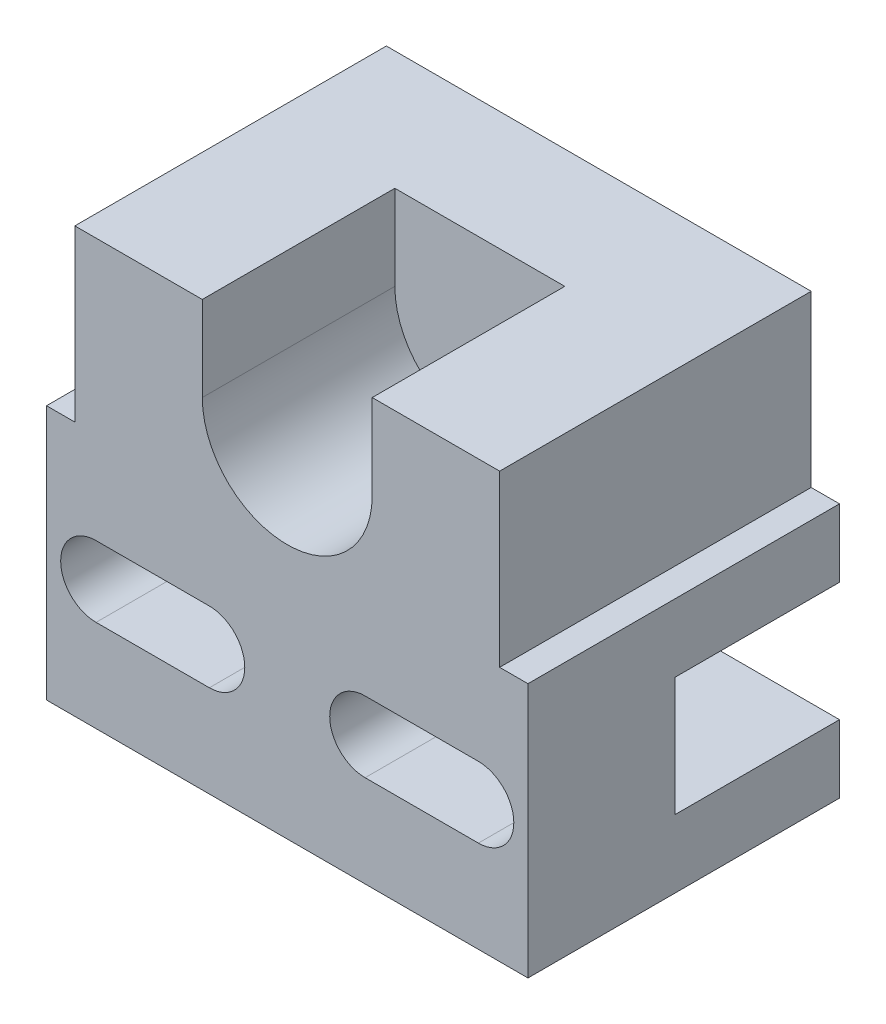
SolidWorks part; units mm, degrees
ref_plane "Front Plane" through (0, 0, 0) normal (0, 0, 1) x (1, 0, 0)
ref_plane "Top Plane" through (0, 0, 0) normal (0, 1, 0) x (1, 0, 0)
ref_plane "Right Plane" through (0, 0, 0) normal (1, 0, 0) x (0, 0, -1)
sketch "Sketch1" plane through (0, 0, 0) normal (0, 0, 1) x (1, 0, 0)
  line L0 (55, 0) -> (-55, 0) construction
  line L1 (-8.5, 0) -> (8.5, 0)
  line L2 (-8.5, 0) -> (-8.5, 9)
  line L3 (-7.5, 15) -> (7.5, 15)
  line L4 (8.5, 0) -> (8.5, 9)
  line L5 (-7.5, 15) -> (-7.5, 9)
  line L6 (-7.5, 9) -> (-8.5, 9)
  line L7 (8.5, 9) -> (7.5, 9)
  line L8 (7.5, 9) -> (7.5, 15)
  dimension "D1" = 17
  dimension "D2" = 15
  dimension "D3" = 15
  dimension "D4" = 9
extrude "Boss-Extrude1" add sketch "Sketch1" along normal blind 11
sketch "Sketch2" plane through (0, 0, 11) normal (0, 0, 1) x (1, 0, 0)
  line L0 (0, 18) -> (0, 12) construction
  line L1 (0, -54.6431) -> (0, 54.6431) construction
  line L2 (3, 18) -> (3, 12)
  line L3 (-3, 18) -> (-3, 12)
  line L4 (55, 0) -> (-55, 0) construction
  line L5 (7.5, 15) -> (-7.5, 15) construction
  arc A0 (3, 18) -> (-3, 18) centre (0, 18) ccw
  arc A1 (-3, 12) -> (3, 12) centre (0, 12) ccw
  point P5 (0, 15)
  dimension "D1" = 6
  dimension "D2" = 12
extrude "Cut-Extrude1" cut sketch "Sketch2" against normal offset from surface (7 mm away) 4 up to face at (0, 8.25, 0)
sketch "Sketch4" plane through (0, 0, 4) normal (0, 0, 1) x (1, 0, 0)
  circle A0 centre (0, 12) radius 1.6
  arc A1 (-3, 12) -> (3, 12) centre (0, 12) ccw construction
  dimension "D1" = 3.2
extrude "Cut-Extrude2" cut sketch "Sketch4" against normal through all
sketch "Sketch5" plane through (0, 0, 11) normal (0, 0, 1) x (1, 0, 0)
  line L0 (0, 0) -> (0, 17.4753) construction
  line L1 (0, -54.6431) -> (0, 54.6431) construction
  line L2 (55, 0) -> (-55, 0) construction
  circle A0 centre (-4.75, 4.5) radius 1.25
  circle A1 centre (4.75, 4.5) radius 1.25
  dimension "D2" = 2.5
  dimension "D1" = 9.5
  dimension "D3" = 4.5
extrude "Cut-Extrude3" cut sketch "Sketch5" against normal through all
sketch "Sketch7" plane through (0, 0, 11) normal (0, 0, 1) x (1, 0, 0)
  line L0 (-6.75, 4.5) -> (-2.75, 4.5) construction
  line L1 (-6.75, 5.75) -> (-2.75, 5.75)
  line L2 (-6.75, 3.25) -> (-2.75, 3.25)
  line L3 (6.75, 4.5) -> (2.75, 4.5) construction
  line L4 (6.75, 3.25) -> (2.75, 3.25)
  line L5 (6.75, 5.75) -> (2.75, 5.75)
  arc A0 (-6.75, 5.75) -> (-6.75, 3.25) centre (-6.75, 4.5) ccw
  arc A1 (-2.75, 3.25) -> (-2.75, 5.75) centre (-2.75, 4.5) ccw
  arc A2 (6.75, 3.25) -> (6.75, 5.75) centre (6.75, 4.5) ccw
  arc A3 (2.75, 5.75) -> (2.75, 3.25) centre (2.75, 4.5) ccw
  circle A4 centre (4.75, 4.5) radius 1.25 construction
  circle A5 centre (-4.75, 4.5) radius 1.25 construction
  point P2 (-4.75, 4.5)
  point P9 (4.75, 4.5)
  dimension "D1" = 4
extrude "Cut-Extrude4" cut sketch "Sketch7" against normal through all
sketch "Sketch8" plane through (0, 0, 0) normal (0, 0, -1) x (-1, 0, 0)
  line L1 (-1.5376, 6.6) -> (-3.9624, 6.6)
  line L2 (-3.9624, 6.6) -> (-5.1749, 4.5)
  line L3 (-5.1749, 4.5) -> (-3.9624, 2.4)
  line L4 (-3.9624, 2.4) -> (-1.5376, 2.4)
  line L5 (-1.5376, 2.4) -> (-0.3251, 4.5)
  line L6 (-0.3251, 4.5) -> (-1.5376, 6.6)
  line L7 (1.5376, 6.6) -> (0.3251, 4.5)
  line L8 (0.3251, 4.5) -> (1.5376, 2.4)
  line L9 (1.5376, 2.4) -> (3.9624, 2.4)
  line L10 (3.9624, 2.4) -> (5.1749, 4.5)
  line L11 (5.1749, 4.5) -> (3.9624, 6.6)
  line L12 (3.9624, 6.6) -> (1.5376, 6.6)
  circle A0 centre (-2.75, 4.5) radius 2.1 construction
  circle A1 centre (2.75, 4.5) radius 2.1 construction
  dimension "D1" = 4.2
extrude "Cut-Extrude5" cut sketch "Sketch8" against normal offset from surface (5.8 mm away) 5.2 up to face at (4.75, 4.5, 11)
sketch "Sketch9" plane through (0, 0, 5.8) normal (0, 0, -1) x (-1, 0, 0)
  line L0 (-3.9624, 2.4) -> (-1.5376, 2.4) construction
  line L1 (1.5376, 6.6) -> (8.5, 6.6)
  line L2 (1.5376, 6.6) -> (1.5376, 2.4)
  line L3 (1.5376, 2.4) -> (8.5, 2.4)
  line L4 (8.5, 6.6) -> (8.5, 2.4)
  line L5 (-1.5376, 6.6) -> (-8.5, 6.6)
  line L6 (-1.5376, 6.6) -> (-1.5376, 2.4)
  line L7 (-1.5376, 2.4) -> (-8.5, 2.4)
  line L8 (-8.5, 6.6) -> (-8.5, 2.4)
  line L9 (-3.9624, 2.4) -> (-1.5376, 2.4) construction
  line L10 (-8.5, 0) -> (-8.5, 9) construction
  line L11 (8.5, 9) -> (8.5, 0) construction
extrude "Cut-Extrude6" cut sketch "Sketch9" along normal up to surface (5.8 mm away) up to face at (-3.8868, 4.5, 0)
sketch "Sketch11" plane through (0, 0, 4) normal (0, 0, 1) x (1, 0, 0)
  line L3 (3, 15) -> (-3, 15)
  line L4 (-3, 15) -> (-3, 12)
  line L5 (3, 12) -> (3, 15)
  line L6 (3, 15) -> (-3, 15)
  line L7 (-3, 15) -> (-3, 12)
  line L8 (3, 12) -> (3, 15)
  arc A1 (-3, 12) -> (3, 12) centre (0, 12) ccw
  arc A2 (-3, 12) -> (3, 12) centre (0, 12) ccw
  dimension "D1" = 0
extrude "Boss-Extrude3" add sketch "Sketch11" along normal blind 0.2
sketch "Sketch12" plane through (0, 0, 5.8) normal (0, 0, -1) x (-1, 0, 0)
  line L0 (0, 8.9) -> (0, 6.9369) construction
  line L1 (1.5, 8.9) -> (1.5, 6.9369)
  line L2 (-1.5, 8.9) -> (-1.5, 6.9369)
  line L3 (0, 2.0631) -> (0, 1.5) construction
  line L4 (1.5, 2.0631) -> (1.5, 1.5)
  line L5 (-1.5, 2.0631) -> (-1.5, 1.5)
  line L6 (1.5376, 6.6) -> (0.3251, 4.5) construction
  line L7 (-0.3251, 4.5) -> (-1.5376, 6.6) construction
  line L8 (-0.3251, 4.5) -> (-1.5376, 6.6) construction
  line L9 (0, 54.6431) -> (0, -54.6431) construction
  line L10 (-1.5376, 2.4) -> (-0.3251, 4.5) construction
  line L12 (8.5, 0) -> (-8.5, 0) construction
  arc A0 (1.5, 8.9) -> (-1.5, 8.9) centre (0, 8.9) ccw
  arc A1 (-1.5, 6.9369) -> (1.5, 6.9369) centre (0, 6.9369) ccw
  arc A2 (1.5, 2.0631) -> (-1.5, 2.0631) centre (0, 2.0631) ccw
  arc A3 (-1.5, 1.5) -> (1.5, 1.5) centre (0, 1.5) ccw
  circle A4 centre (0, 12) radius 1.6 construction
  point P2 (0, 7.9184)
  point P7 (0, 1.7816)
  dimension "D1" = 3
extrude "Boss-Extrude4" add sketch "Sketch12" along normal offset from surface (7.3 mm away) 1.5 up to face at (1.6, 12, 0) offset beyond the face yes
sketch "Sketch13" plane through (0, 0, 5.8) normal (0, 0, 1) x (1, 0, 0)
  arc A2 (1.4273, 9.3613) -> (-1.4273, 9.3613) centre (0, 8.9) ccw
  arc A3 (-1.4273, 9.3613) -> (1.4273, 9.3613) centre (0, 12) ccw
  arc A4 (1.4273, 9.3613) -> (-1.4273, 9.3613) centre (0, 8.9) ccw
  arc A5 (-1.4273, 9.3613) -> (1.4273, 9.3613) centre (0, 12) ccw
  dimension "D1" = 0
extrude "Cut-Extrude7" cut sketch "Sketch13" against normal up to surface (1.6 mm away) up to face at (0, 12.2214, 4.2)
